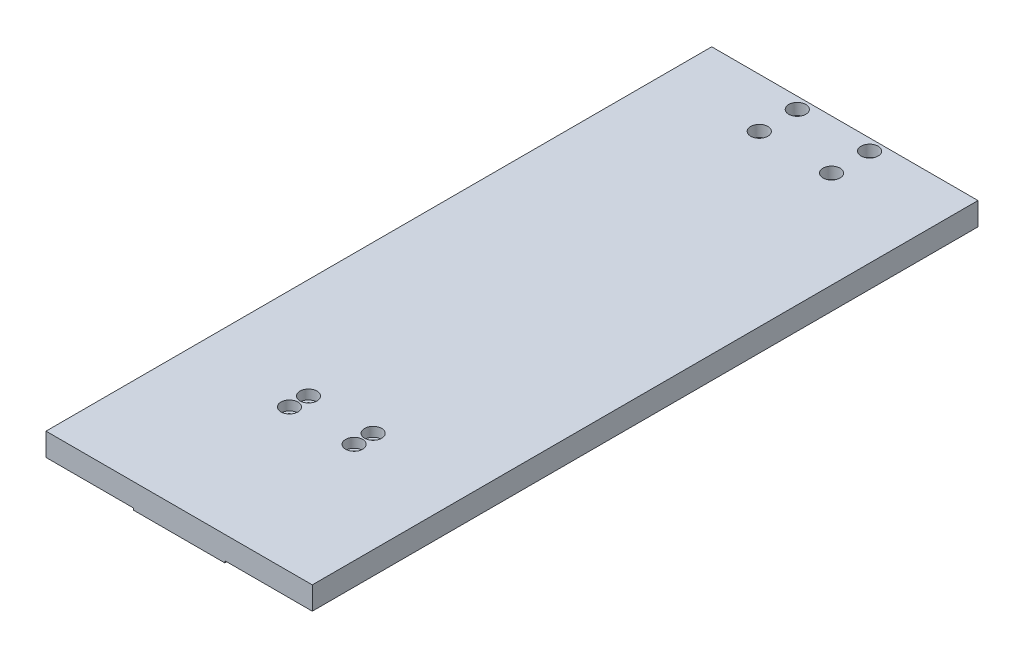
SolidWorks part; units mm, degrees
material "1.0037 (S235JR)"
ref_plane "Płaszczyzna przednia" through (0, 0, 0) normal (0, 0, 1) x (1, 0, 0)
ref_plane "Płaszczyzna górna" through (0, 0, 0) normal (0, 1, 0) x (1, 0, 0)
ref_plane "Płaszczyzna prawa" through (0, 0, 0) normal (1, 0, 0) x (0, 0, -1)
sketch "Szkic1" plane through (0, 0, 0) normal (0, 1, 0) x (1, 0, 0)
  line L1 (0, 0) -> (140, 0)
  line L2 (0, 0) -> (0, 350)
  line L3 (0, 350) -> (140, 350)
  line L4 (140, 0) -> (140, 350)
  dimension "D1" = 140
  dimension "D2" = 350
extrude "Dodanie-wyciągnięcie1" add sketch "Szkic1" along normal blind 13
sketch "Szkic2" plane through (0, 0, 0) normal (0, -1, 0) x (1, 0, 0)
  line L0 (0, 0) -> (140, 0) construction
  line L1 (0, -350) -> (46, -350)
  line L2 (0, -350) -> (0, 0)
  line L3 (0, 0) -> (46, 0)
  line L4 (46, -350) -> (46, 0)
  line L6 (140, -350) -> (94, -350)
  line L7 (140, -350) -> (140, 0)
  line L8 (140, 0) -> (94, 0)
  line L9 (94, -350) -> (94, 0)
  dimension "D1" = 46
extrude "Wytnij-wyciągnięcie1" cut sketch "Szkic2" against normal blind 1
hole_wizard "Otwór gwintowany M5x0.81" positions "Szkic11" profile "Szkic10" tap size "M5x0.8" standard "Ansi Metric"
sketch "Szkic11" plane through (0, 0, -350) normal (0, 0, -1) x (-1, 0, 0)
  point P0 (-130, 7)
  point P3 (-105, 7)
  point P6 (-35, 7)
  point P9 (-10, 7)
sketch "Szkic10" plane through (130, 7, -350) normal (1, 0, 0) x (0, 1, 0)
  line L0 (0, 0) -> (0, 36.2618)
  line L1 (0, 36.2618) -> (2.1, 35)
  line L2 (2.1, 35) -> (2.1, 0)
  line L5 (2.1, 0) -> (0, 0)
  line L10 (0, 36.2618) -> (-2.1, 35) construction
  line L11 (0, -6.35) -> (0, 107.95) construction
  dimension "Średnica wiertła gwintu" = 4.2
  dimension "Głębokość otworu gwintowanego" = 35
  dimension "Kąt wiertła" = 118
sketch "Szkic12" plane through (0, 0, 0) normal (0, -1, 0) x (-1, 0, 0)
  line L0 (-46, 350) -> (-46, 0) construction
  line L1 (-94, 60) -> (-46, 60)
  line L2 (-94, 60) -> (-94, 100)
  line L3 (-94, 100) -> (-46, 100)
  line L4 (-46, 60) -> (-46, 100)
  line L5 (-94, 350) -> (-46, 350) construction
  line L6 (-94, 350) -> (-46, 350)
  line L7 (-94, 350) -> (-94, 310)
  line L8 (-94, 310) -> (-46, 310)
  line L9 (-46, 350) -> (-46, 310)
  line L10 (-94, 0) -> (-94, 350) construction
  line L11 (-46, 0) -> (-94, 0) construction
  dimension "D1" = 40
  dimension "D2" = 40
  dimension "D5" = 60
extrude "Wytnij-wyciągnięcie3" cut sketch "Szkic12" against normal blind 1
hole_wizard "Pogłębienie walcowe pod M5 Wkręt do części metalowych z łbem sześciokątnym1" positions "Szkic14" profile "Szkic13" counterbore size "M5" standard "Ansi Metric" end condition through all
sketch "Szkic14" plane through (0, 13, 0) normal (0, 1, 0) x (1, 0, 0)
  circle A0 centre (51, 344) radius 2.1 construction
  circle A1 centre (89, 344) radius 2.1 construction
  circle A2 centre (51, 324) radius 2.1 construction
  circle A3 centre (89, 324) radius 2.1 construction
  point P0 (51, 344)
  point P2 (89, 344)
  point P4 (51, 324)
  point P6 (89, 324)
sketch "Szkic13" plane through (51, 13, -344) normal (1, 0, 0) x (0, 0, 1)
  line L0 (0, 0) -> (0, 13)
  line L1 (0, 13) -> (2.75, 13)
  line L3 (2.75, 13) -> (2.75, 6)
  line L4 (2.75, 6) -> (4.5, 6)
  line L5 (4.5, 6) -> (4.5, 0)
  line L7 (4.5, 0) -> (0, 0)
  line L11 (0, -6.35) -> (0, 107.95) construction
  dimension "Średnica otworu na wylot" = 5.5
  dimension "Głębokość otworu na wylot" = 13
  dimension "Średnica pogłębienia walcowego" = 9
  dimension "Głębokość pogłębienia walcowego" = 6
hole_wizard "Pogłębienie walcowe pod M5 Wkręt do części metalowych z łbem sześciokątnym2" positions "Szkic16" profile "Szkic15" counterbore size "M5" standard "Ansi Metric" end condition through all
sketch "Szkic16" plane through (0, 13, 0) normal (0, 1, 0) x (1, 0, 0)
  circle A0 centre (53, 85) radius 2.1 construction
  circle A1 centre (53, 75) radius 2.1 construction
  circle A2 centre (87, 75) radius 2.1 construction
  circle A3 centre (87, 85) radius 2.1 construction
  point P0 (53, 85)
  point P2 (87, 85)
  point P4 (53, 75)
  point P6 (87, 75)
sketch "Szkic15" plane through (53, 13, -85) normal (1, 0, 0) x (0, 0, 1)
  line L0 (0, 0) -> (0, 13)
  line L1 (0, 13) -> (2.75, 13)
  line L3 (2.75, 13) -> (2.75, 5)
  line L4 (2.75, 5) -> (4.5, 5)
  line L5 (4.5, 5) -> (4.5, 0)
  line L7 (4.5, 0) -> (0, 0)
  line L11 (0, -6.35) -> (0, 107.95) construction
  dimension "Średnica otworu na wylot" = 5.5
  dimension "Głębokość otworu na wylot" = 13
  dimension "Średnica pogłębienia walcowego" = 9
  dimension "Głębokość pogłębienia walcowego" = 5
